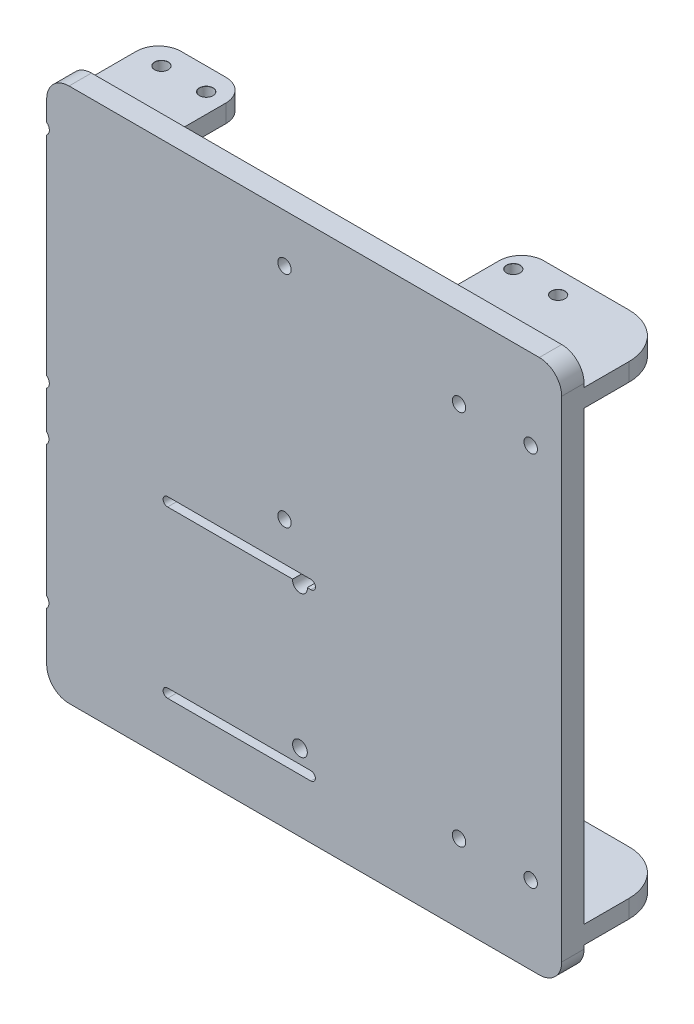
SolidWorks part; units mm, degrees
ref_plane "前视基准面" through (0, 0, 0) normal (0, 0, 1) x (1, 0, 0)
ref_plane "上视基准面" through (0, 0, 0) normal (0, 1, 0) x (1, 0, 0)
ref_plane "右视基准面" through (0, 0, 0) normal (1, 0, 0) x (0, 0, -1)
other "Configuration Table"
sketch "草图1" plane through (0, 0, 0) normal (0, 0, 1) x (1, 0, 0)
  line L1 (-32.1975, 60.1854) -> (82.8025, 60.1854)
  line L2 (-32.1975, 60.1854) -> (-32.1975, -59.2146)
  line L3 (-32.1975, -59.2146) -> (82.8025, -59.2146)
  line L4 (82.8025, 60.1854) -> (82.8025, -59.2146)
  dimension "D1" = 119.4
  dimension "D2" = 115
extrude "凸台-拉伸1" add sketch "草图1" along normal blind 5
sketch "草图2" plane through (0, 0, 0) normal (0, 0, -1) x (-1, 0, 0)
  line L0 (32.1975, 60.1854) -> (32.1975, -59.2146) construction
  line L1 (32.1975, -53.4146) -> (-82.8025, -53.4146)
  line L2 (32.1975, -53.4146) -> (32.1975, -49.4146)
  line L3 (32.1975, -49.4146) -> (-82.8025, -49.4146)
  line L4 (-82.8025, -53.4146) -> (-82.8025, -49.4146)
  line L7 (32.1975, 50.3854) -> (-82.8025, 50.3854)
  line L8 (32.1975, 50.3854) -> (32.1975, 54.3854)
  line L9 (32.1975, 54.3854) -> (-82.8025, 54.3854)
  line L10 (-82.8025, 50.3854) -> (-82.8025, 54.3854)
  line L11 (-82.8025, 60.1854) -> (32.1975, 60.1854) construction
  line L12 (32.1975, -59.2146) -> (-82.8025, -59.2146) construction
  line L13 (-82.8025, -59.2146) -> (-82.8025, 60.1854) construction
  line L14 (-48.8025, 54.3854) -> (-48.8025, 50.3854)
  line L16 (12.1975, 54.3854) -> (12.1975, 50.3854)
  line L17 (12.1975, -49.4146) -> (12.1975, -53.4146)
  line L18 (-48.8025, -49.4146) -> (-48.8025, -53.4146)
  point P6 (-82.8025, -51.4146)
  point P27 (-82.8025, 52.3854)
  line M11 (32.1975, -59.2146) -> (32.1975, 60.1854)
  line M13 (-82.8025, 60.1854) -> (-82.8025, -59.2146)
  dimension "D1" = 5.8
  dimension "D2" = 4
  dimension "D3" = 5.8
  dimension "D4" = 4
  dimension "D5" = 20
  dimension "D6" = 20
  dimension "D7" = 34
extrude "凸台-拉伸2" add sketch "草图2" along normal blind 20 contours L9 L16 L7 M11 | L14 L9 L7 M13 | L18 L3 L1 M13 | L3 L17 L1 M11
hole_wizard "Ø3.0mm 暗销孔1" positions "草图3" profile "草图4" hole size "Ø3.0" standard "IS" end condition through all
sketch "草图3" plane through (0, 54.3854, 0) normal (0, 1, 0) x (1, 0, 0)
  point P0 (62, 15)
  point P3 (-16.57, 15)
  point P6 (-26.57, 15)
  point P9 (52, 15)
sketch "草图4" plane through (62, 54.3854, -15) normal (1, 0, 0) x (0, 0, 1)
  line L0 (0, 0) -> (0, 113.6)
  line L1 (0, 113.6) -> (1.5, 113.6)
  line L2 (1.5, 113.6) -> (1.5, 0.025)
  line L3 (1.5, 0.025) -> (1.525, 0)
  line L5 (1.525, 0) -> (0, 0)
  line L6 (-1.5, 0.025) -> (-1.525, 0) construction
  line L11 (0, -6.35) -> (0, 107.95) construction
  dimension "通孔孔直径" = 3
  dimension "通孔孔深度" = 113.6
  dimension "近端锥形沉头孔直径" = 3.05
  dimension "近端锥形沉头孔角度" = 90
fillet "圆角1" radius 10 2 edges at (82.8025, -51.4146, -20) (82.8025, 52.3854, -20)
fillet "圆角2" radius 5 6 edges at (-12.1975, 52.3854, -20) (-32.1975, 52.3854, -20) (-12.1975, -51.4146, -20) (-32.1975, -51.4146, -20) (48.8025, 52.3854, -20) (48.8025, -51.4146, -20)
fillet "圆角3" radius 5 4 edges at (82.8025, -59.2146, 2.5) (82.8025, 60.1854, 2.5) (-32.1975, 60.1854, 2.5) (-32.1975, -59.2146, 2.5)
sketch "草图5" plane through (0, 0, 5) normal (0, 0, 1) x (1, 0, 0)
  circle A0 centre (-33.1003, 49.4399) radius 1.5
  circle A1 centre (20.8997, 49.4392) radius 1.4992
  circle A2 centre (20.8997, 0.4399) radius 1.5
  circle A3 centre (-33.1003, 0.4399) radius 1.5
  circle A4 centre (59.8751, 42.1981) radius 1.5
  circle A5 centre (75.8751, 42.1981) radius 1.5
  circle A6 centre (59.8751, -41.8019) radius 1.5
  circle A7 centre (75.8751, -41.8019) radius 1.5
  circle A8 centre (-33.3467, -42.1129) radius 1.65
  circle A9 centre (-33.3467, -10.4129) radius 1.65
  circle A10 centre (24.3533, -10.4129) radius 1.65
  circle A11 centre (24.3533, -42.1129) radius 1.65
extrude "切除-拉伸1" cut sketch "草图5" against normal through all
sketch "草图6" plane through (0, 0, 5) normal (0, 0, 1) x (1, 0, 0)
  line L0 (-5.1975, -9.2146) -> (26.8025, -9.2146) construction
  line L1 (-5.1975, -8.2146) -> (26.8025, -8.2146)
  line L2 (-5.1975, -10.2146) -> (26.8025, -10.2146)
  line L3 (-5.1975, -46.2146) -> (26.8025, -46.2146) construction
  line L4 (-5.1975, -45.2146) -> (26.8025, -45.2146)
  line L5 (-5.1975, -47.2146) -> (26.8025, -47.2146)
  line L6 (-32.1975, 55.1854) -> (-32.1975, 50.6379) construction
  line L7 (-27.1975, -59.2146) -> (77.8025, -59.2146) construction
  arc A0 (-5.1975, -8.2146) -> (-5.1975, -10.2146) centre (-5.1975, -9.2146) ccw
  arc A1 (26.8025, -10.2146) -> (26.8025, -8.2146) centre (26.8025, -9.2146) ccw
  arc A2 (-5.1975, -45.2146) -> (-5.1975, -47.2146) centre (-5.1975, -46.2146) ccw
  arc A3 (26.8025, -47.2146) -> (26.8025, -45.2146) centre (26.8025, -46.2146) ccw
  point P2 (10.8025, -9.2146)
  point P7 (10.8025, -46.2146)
  dimension "D1" = 2
  dimension "D2" = 2
  dimension "D3" = 35
  dimension "D4" = 32
  dimension "D5" = 27
  dimension "D6" = 12
extrude "切除-拉伸2" cut sketch "草图6" against normal through all
